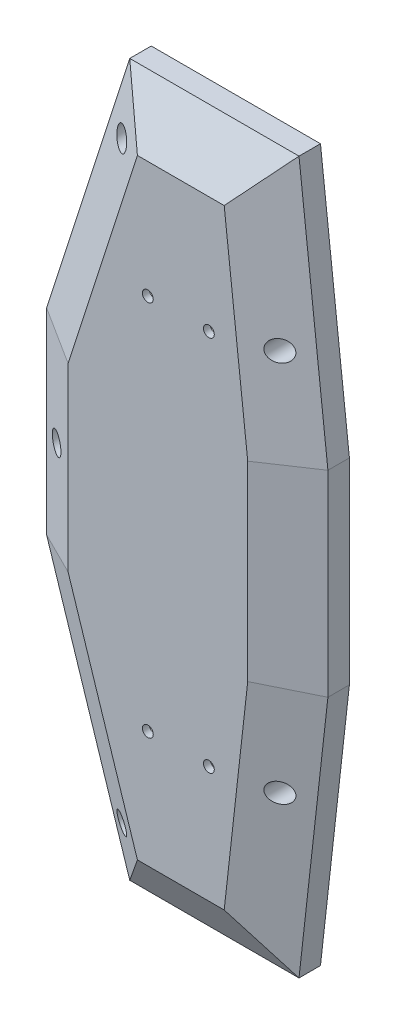
SolidWorks part; units mm, degrees
material "ABS"
ref_plane "Front Plane" through (0, 0, 0) normal (0, 0, 1) x (1, 0, 0)
ref_plane "Top Plane" through (0, 0, 0) normal (0, 1, 0) x (1, 0, 0)
ref_plane "Right Plane" through (0, 0, 0) normal (1, 0, 0) x (0, 0, -1)
sketch "Sketch1" plane through (0, 0, 0) normal (0, 0, 1) x (1, 0, 0)
  line L0 (-24.9678, 105) -> (-49.5, 29)
  line L1 (-49.5, 29) -> (-49.5, -29)
  line L2 (-49.5, -29) -> (-24.9678, -105)
  line L3 (-24.9678, -105) -> (24.9678, -105)
  line L4 (24.9678, -105) -> (33.5, -29)
  line L5 (33.5, -29) -> (33.5, 29)
  line L6 (33.5, 29) -> (24.9678, 105)
  line L7 (24.9678, 105) -> (-24.9678, 105)
extrude "Extrude1" add sketch "Sketch1" along normal blind 15
chamfer "Chamfer1" distance 15 angle 30 8 edges at (29.2339, 67, 15) (33.5, 0, 15) (29.2339, -67, 15) (0, -105, 15) (0, 105, 15) (-37.2339, 67, 15) (-49.5, 0, 15) (-37.2339, -67, 15)
shell "Shell1" thickness 2
ref_plane "Plane1" through (0, 0, 3) normal (0, 0, -1) x (-1, 0, 0)
sketch "Sketch2" plane through (0, 0, 0) normal (0, 0, -1) x (-1, 0, 0)
  circle A0 centre (23.2777, 87.4482) radius 1.6
  circle A1 centre (23.2777, 87.4482) radius 4
  circle A2 centre (-23.3725, 56.4663) radius 1.6
  circle A3 centre (-23.3725, 56.4663) radius 4
  circle A4 centre (42.5, 0) radius 1.6
  circle A5 centre (42.5, 0) radius 4
  circle A6 centre (-23.3725, -56.4663) radius 1.6
  circle A7 centre (-23.3725, -56.4663) radius 4
  circle A8 centre (23.2777, -87.4482) radius 1.6
  circle A9 centre (23.2777, -87.4482) radius 4
  dimension "D1" = 3.2
extrude "Extrude2" add sketch "Sketch2" against normal up to next
sketch "Sketch3" plane through (0, 0, 3) normal (0, 0, -1) x (-1, 0, 0)
  circle A0 centre (23.2777, 87.4482) radius 3
  circle A1 centre (-23.3725, 56.4663) radius 3
  circle A2 centre (-23.3725, -56.4663) radius 3
  circle A3 centre (23.2777, -87.4482) radius 3
  circle A4 centre (42.5, 0) radius 3
  dimension "D1" = 6
extrude "Cut-Extrude1" cut sketch "Sketch3" against normal blind 15
sketch "Sketch5" plane through (0, 0, 19) normal (0, 0, 1) x (1, 0, 0)
  circle A0 centre (-10.9678, 55.6) radius 1.6 construction
  circle A1 centre (7.0322, 55.6) radius 1.6 construction
  circle A2 centre (7.0322, -55.6) radius 1.6 construction
  circle A3 centre (-10.9678, -55.6) radius 1.6 construction
  circle A4 centre (-10.9678, 55.6) radius 1.6
  circle A5 centre (7.0322, 55.6) radius 1.6
  circle A6 centre (7.0322, -55.6) radius 1.6
  circle A7 centre (-10.9678, -55.6) radius 1.6
extrude "Cut-Extrude2" cut sketch "Sketch5" against normal blind 20
